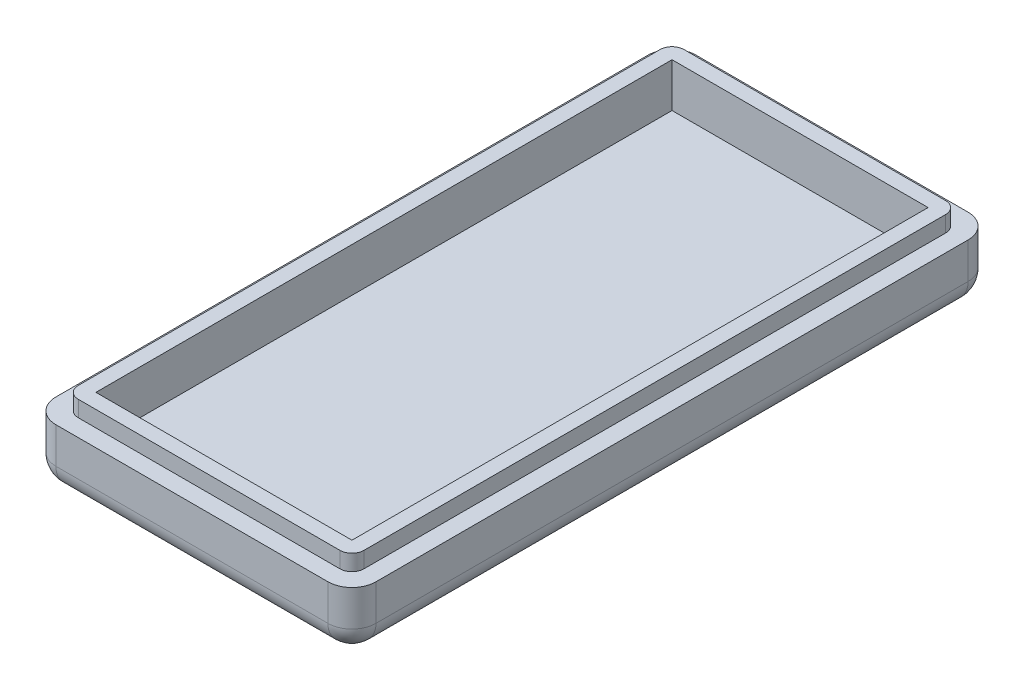
SolidWorks part; units mm, degrees
ref_plane "Front Plane" through (0, 0, 0) normal (0, 0, 1) x (1, 0, 0)
ref_plane "Top Plane" through (0, 0, 0) normal (0, 1, 0) x (1, 0, 0)
ref_plane "Right Plane" through (0, 0, 0) normal (1, 0, 0) x (0, 0, -1)
sketch "Sketch1" plane through (0, 0, 0) normal (0, 0, 1) x (1, 0, 0)
  line L1 (0, 0) -> (40, 0)
  line L2 (0, 0) -> (0, 7.5)
  line L3 (0, 7.5) -> (40, 7.5)
  line L4 (40, 0) -> (40, 7.5)
  dimension "D1" = 40
  dimension "D2" = 7.5
extrude "Boss-Extrude1" add sketch "Sketch1" along normal blind 80
shell "Shell1" thickness 4
fillet "Fillet1" radius 3 8 edges at (20, 0, 80) (0, 3.75, 80) (0, 0, 40) (40, 3.75, 80) (40, 0, 40) (40, 3.75, 0) (20, 0, 0) (0, 3.75, 0)
sketch "Sketch2" plane through (0, 7.5, 0) normal (0, 1, 0) x (1, 0, 0)
  line L10 (36, -4) -> (4, -4)
  line L11 (4, -4) -> (4, -76)
  line L12 (4, -76) -> (36, -76)
  line L13 (36, -76) -> (36, -4)
  line L14 (2.15, -77.85) -> (37.85, -77.85)
  line L15 (37.85, -77.85) -> (37.85, -2.15)
  line L16 (37.85, -2.15) -> (2.15, -2.15)
  line L17 (2.15, -2.15) -> (2.15, -77.85)
  line L18 (3.65, -77.85) -> (36.35, -77.85)
  line L19 (37.85, -76.35) -> (37.85, -3.65)
  line L20 (36.35, -2.15) -> (3.65, -2.15)
  line L21 (2.15, -3.65) -> (2.15, -76.35)
  line L22 (2.15, -2.15) -> (2.15, -77.85) construction
  line L23 (2.15, -77.85) -> (37.85, -77.85) construction
  line L24 (37.85, -77.85) -> (37.85, -2.15) construction
  line L25 (37.85, -2.15) -> (2.15, -2.15) construction
  arc A0 (2.15, -76.35) -> (3.65, -77.85) centre (3.65, -76.35) ccw
  arc A1 (37.85, -76.35) -> (36.35, -77.85) centre (36.35, -76.35) cw
  arc A2 (36.35, -2.15) -> (37.85, -3.65) centre (36.35, -3.65) cw
  arc A3 (2.15, -3.65) -> (3.65, -2.15) centre (3.65, -3.65) cw
  dimension "D3" = 1.5
  dimension "D1" = 1.85
  dimension "D2" = 1.85
extrude "Boss-Extrude2" add sketch "Sketch2" along normal blind 2
